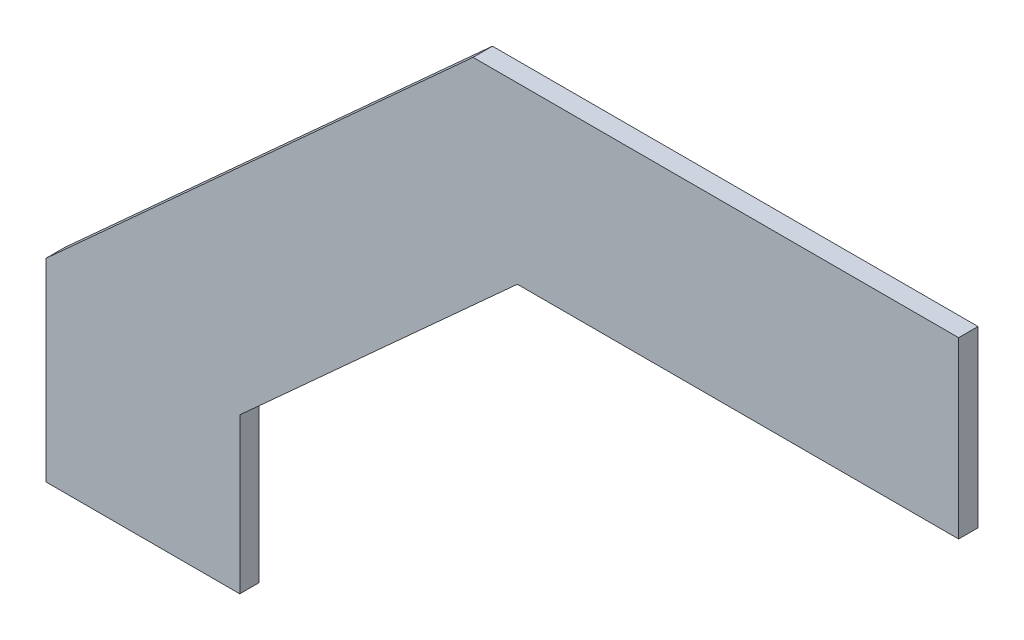
SolidWorks part; units mm, degrees
material "PBT General Purpose"
ref_plane "Front Plane" through (0, 0, 0) normal (0, 0, 1) x (1, 0, 0)
ref_plane "Top Plane" through (0, 0, 0) normal (0, 1, 0) x (1, 0, 0)
ref_plane "Right Plane" through (0, 0, 0) normal (1, 0, 0) x (0, 0, -1)
sketch "Sketch1" plane through (0, 0, 0) normal (0, 0, 1) x (1, 0, 0)
  line L7 (0, 0) -> (1, 0)
  line L8 (1, 0) -> (1, 0.8)
  line L9 (1, 0.8) -> (2.4327, 2.1)
  line L10 (2.4327, 2.1) -> (4.71, 2.1)
  line L11 (4.71, 2.1) -> (4.71, 3)
  line L12 (4.71, 3) -> (2.2042, 3)
  line L13 (2.2042, 3) -> (0, 1)
  line L14 (0, 1) -> (0, 0)
  point P2 (1.41, 1.5)
  point P8 (1, 1.3505)
  point P11 (2.0448, 2)
  point P12 (2.3199, 2)
  point P13 (2.4327, 2.1)
  dimension "D1" = 1
  dimension "D2" = 0.9
  dimension "D3" = 0.8
  dimension "D4" = 3.71
  dimension "D5" = 1
  dimension "D6" = 3
extrude "Boss-Extrude1" add sketch "Sketch1" along normal mid plane 0.1 contours L10 L11 L12 L13 L14 L7 L8 L9
